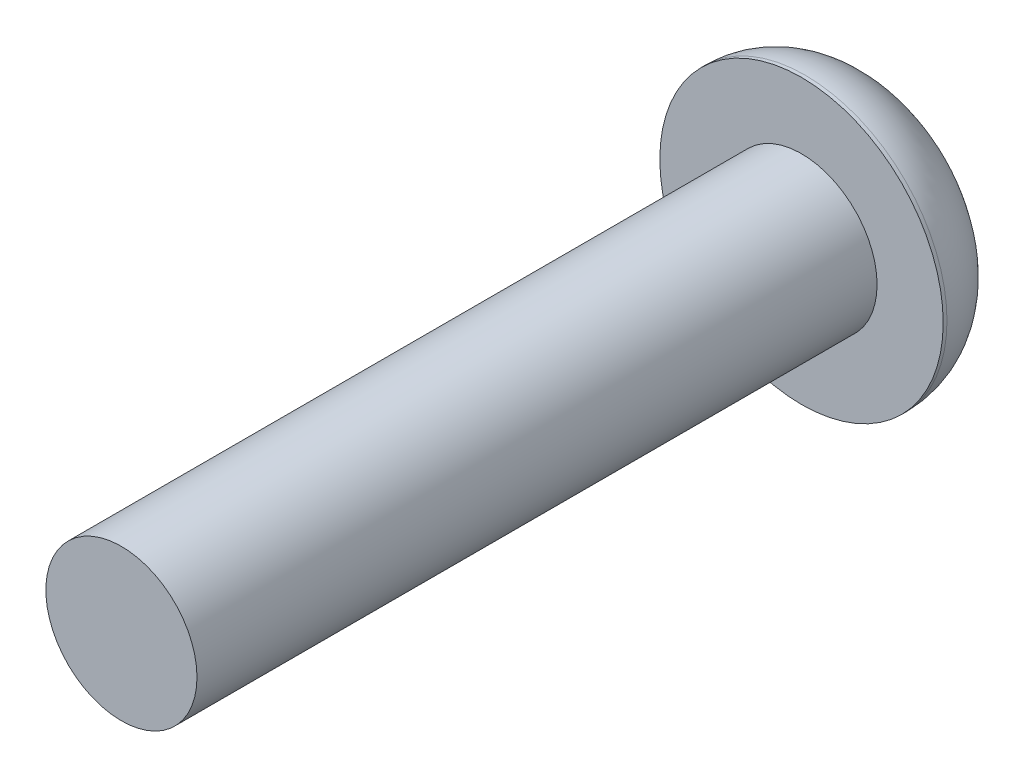
SolidWorks part; units mm, degrees
ref_plane "前视基准面" through (0, 0, 0) normal (0, 0, 1) x (1, 0, 0)
ref_plane "上视基准面" through (0, 0, 0) normal (0, 1, 0) x (1, 0, 0)
ref_plane "右视基准面" through (0, 0, 0) normal (1, 0, 0) x (0, 0, -1)
sketch "草图1" plane through (0, 0, 0) normal (0, 0, 1) x (1, 0, 0)
  circle A0 centre (0, 0) radius 2
extrude "凸台-拉伸1" add sketch "草图1" along normal blind 18
sketch "草图2" plane through (0, 0, 0) normal (0, 0, -1) x (-1, 0, 0)
  circle A0 centre (0, 0) radius 3.75
extrude "凸台-拉伸2" add sketch "草图2" along normal blind 2.1
fillet "圆角1" radius 2 1 edges at (-3.75, 0, -2.1)
